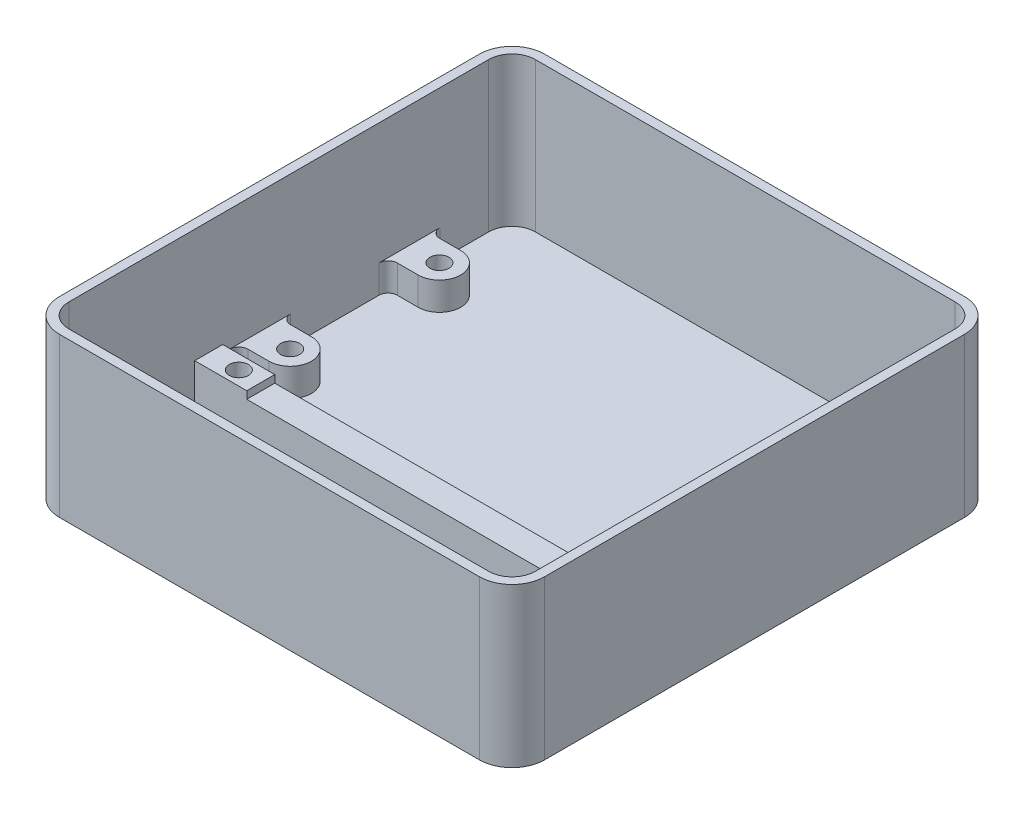
SolidWorks part; units mm, degrees
ref_plane "Front Plane" through (0, 0, 0) normal (0, 0, 1) x (1, 0, 0)
ref_plane "Top Plane" through (0, 0, 0) normal (0, 1, 0) x (1, 0, 0)
ref_plane "Right Plane" through (0, 0, 0) normal (1, 0, 0) x (0, 0, -1)
sketch "Sketch1" plane through (0, 0, 0) normal (0, 1, 0) x (1, 0, 0)
  line L1 (-45, 50) -> (45, 50)
  line L2 (-50, 45) -> (-50, -45)
  line L3 (-45, -50) -> (45, -50)
  line L4 (50, 45) -> (50, -45)
  line L5 (-50, 50) -> (50, -50) construction
  line L6 (-50, -50) -> (50, 50) construction
  arc A0 (-50, -45) -> (-45, -50) centre (-45, -45) ccw
  arc A1 (45, -50) -> (50, -45) centre (45, -45) ccw
  arc A2 (45, 50) -> (50, 45) centre (45, 45) cw
  arc A3 (-45, 50) -> (-50, 45) centre (-45, 45) ccw
  point P0 (0, 0)
  dimension "D1" = 5
  dimension "D2" = 100
  dimension "D3" = 100
extrude "Boss-Extrude1" add sketch "Sketch1" along normal blind 32
shell "Shell1" thickness 2
sketch "Sketch2" plane through (0, 0, 0) normal (0, 1, 0) x (1, 0, 0)
  line L0 (45, 50) -> (-45, 50) construction
  line L1 (-43.55, 28) -> (43.55, 28) construction
  line L2 (-43.55, 28) -> (-43.55, -4) construction
  line L3 (-43.55, -4) -> (43.55, -4) construction
  line L4 (43.55, 28) -> (43.55, -4) construction
  line L5 (-43.55, 28) -> (43.55, -4) construction
  line L6 (-43.55, -4) -> (43.55, 28) construction
  line L7 (-43.55, 32.55) -> (-50, 32.55)
  line L8 (-50, 45) -> (-50, -45) construction
  line L9 (-50, 32.55) -> (-50, 23.45)
  line L10 (-50, 23.45) -> (-43.55, 23.45)
  line L11 (-43.55, 0.55) -> (-50, 0.55)
  line L12 (-50, 45) -> (-50, -45) construction
  line L13 (-50, 0.55) -> (-50, -8.55)
  line L14 (-50, -8.55) -> (-43.55, -8.55)
  line L15 (43.55, 0.55) -> (50, 0.55)
  line L16 (50, -45) -> (50, 45) construction
  line L17 (50, 0.55) -> (50, -8.55)
  line L18 (50, -45) -> (50, 45) construction
  line L19 (50, -8.55) -> (43.55, -8.55)
  line L20 (43.55, 32.55) -> (50, 32.55)
  line L21 (50, 32.55) -> (50, 23.45)
  line L22 (50, 23.45) -> (43.55, 23.45)
  line L24 (-50, -12) -> (50, -12)
  line L25 (-50, -12) -> (-50, -18)
  line L26 (-50, -18) -> (50, -18)
  line L27 (50, -12) -> (50, -18)
  arc A0 (-43.55, 23.45) -> (-43.55, 32.55) centre (-43.55, 28) ccw
  circle A1 centre (-43.55, 28) radius 2.05
  arc A2 (-43.55, -8.55) -> (-43.55, 0.55) centre (-43.55, -4) ccw
  circle A3 centre (-43.55, -4) radius 2.05
  arc A4 (43.55, 32.55) -> (43.55, 23.45) centre (43.55, 28) ccw
  circle A5 centre (43.55, 28) radius 2.05
  arc A6 (43.55, 0.55) -> (43.55, -8.55) centre (43.55, -4) ccw
  circle A7 centre (43.55, -4) radius 2.05
  arc A8 (-43.55, 32.55) -> (-43.55, 23.45) centre (-43.55, 28) ccw construction
  arc A9 (-43.55, 0.55) -> (-43.55, -8.55) centre (-43.55, -4) ccw construction
  arc A10 (43.55, -8.55) -> (43.55, 0.55) centre (43.55, -4) ccw construction
  arc A11 (43.55, 23.45) -> (43.55, 32.55) centre (43.55, 28) ccw construction
  point P0 (0, 12)
  point P40 (0, 0)
  dimension "D3" = 4.1
  dimension "D4" = 2.5
  dimension "D1" = 32
  dimension "D2" = 87.1
  dimension "D5" = 22
  dimension "D6" = 8
  dimension "D7" = 6
extrude "Boss-Extrude2" add sketch "Sketch2" along normal blind 6
fillet "Fillet1" radius 2 8 edges at (50, 3, -32.55) (50, 3, -23.45) (50, 3, -0.55) (50, 3, 8.55) (-50, 3, 8.55) (-50, 3, -0.55) (-50, 3, -32.55) (-50, 3, -23.45)
sketch "Sketch3" plane through (0, 6, 0) normal (0, 1, 0) x (1, 0, 0)
  line L0 (-50, -18) -> (50, -18) construction
  line L1 (-50, -12) -> (-38.85, -12)
  line L2 (-50, -12) -> (-50, -18)
  line L3 (-50, -18) -> (-38.85, -18)
  line L4 (-38.85, -12) -> (-38.85, -18)
  line L6 (50, -12) -> (38.85, -12)
  line L7 (50, -12) -> (50, -18)
  line L8 (50, -18) -> (38.85, -18)
  line L9 (38.85, -12) -> (38.85, -18)
  dimension "D1" = 77.7
extrude "Boss-Extrude3" add sketch "Sketch3" along normal blind 1.6
sketch "Sketch4" plane through (0, 7.6, 0) normal (0, 1, 0) x (1, 0, 0)
  line L0 (-38.85, -18) -> (-38.85, -12) construction
  line L1 (-43.55, -4) -> (-43.55, -15) construction
  line L2 (43.55, -4) -> (43.55, -15) construction
  circle A0 centre (-43.55, -15) radius 2.05
  circle A1 centre (43.55, -15) radius 2.05
  circle A2 centre (-43.55, -4) radius 2.05 construction
  point P6 (-38.85, -15)
extrude "Cut-Extrude1" cut sketch "Sketch4" against normal up to surface (7.6 mm away) up to face at (0, 0, -15.2024)
